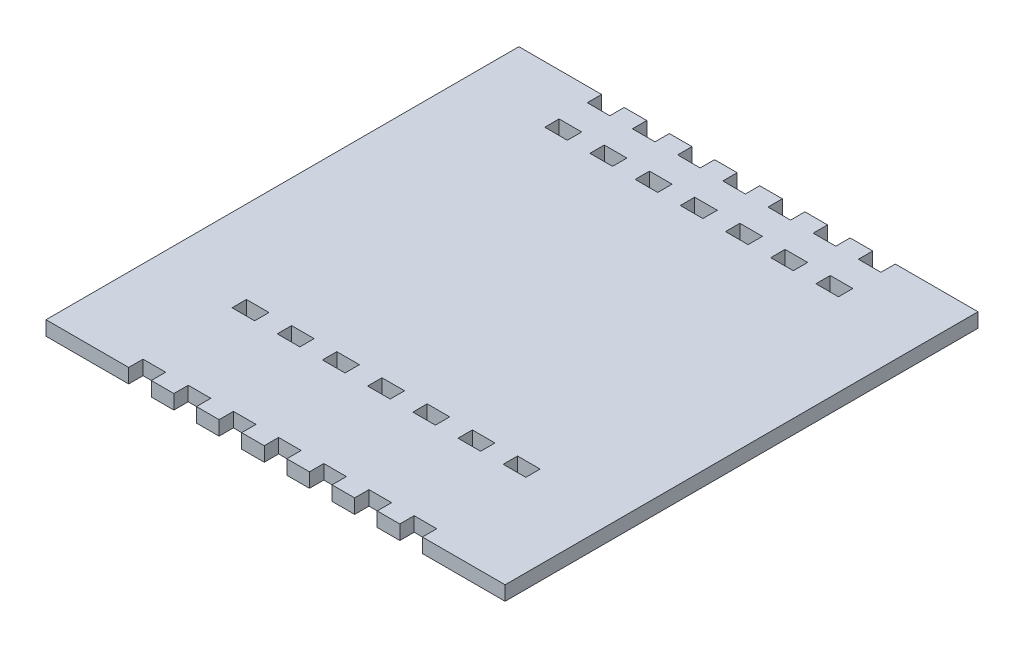
SolidWorks part; units mm, degrees
ref_plane "Front Plane" through (0, 0, 0) normal (0, 0, 1) x (1, 0, 0)
ref_plane "Top Plane" through (0, 0, 0) normal (0, 1, 0) x (1, 0, 0)
ref_plane "Right Plane" through (0, 0, 0) normal (1, 0, 0) x (0, 0, -1)
sketch "Sketch1" plane through (0, 0, 0) normal (0, 1, 0) x (1, 0, 0)
  line L0 (-34.4609, -90.3438) -> (-34.4609, -87.1688)
  line L1 (-34.4609, 14.3042) -> (-52.7609, 14.3042)
  line L2 (-52.7609, 14.3042) -> (-52.7609, -90.3438)
  line L3 (-52.7609, -90.3438) -> (-34.4609, -90.3438)
  line L4 (48.8391, 14.3042) -> (48.8391, -90.3438)
  line L5 (-34.4609, -87.1688) -> (-29.4609, -87.1688)
  line L6 (-29.4609, -87.1688) -> (-29.4609, -90.3438)
  line L7 (-19.4609, -87.1688) -> (-19.4609, -90.3438)
  line L8 (-24.4609, -87.1688) -> (-19.4609, -87.1688)
  line L9 (-24.4609, -90.3438) -> (-24.4609, -87.1688)
  line L10 (-9.4609, -87.1688) -> (-9.4609, -90.3438)
  line L11 (-14.4609, -87.1688) -> (-9.4609, -87.1688)
  line L12 (-14.4609, -90.3438) -> (-14.4609, -87.1688)
  line L13 (0.5391, -87.1688) -> (0.5391, -90.3438)
  line L14 (-4.4609, -87.1688) -> (0.5391, -87.1688)
  line L15 (-4.4609, -90.3438) -> (-4.4609, -87.1688)
  line L16 (10.5391, -87.1688) -> (10.5391, -90.3438)
  line L17 (5.5391, -87.1688) -> (10.5391, -87.1688)
  line L18 (5.5391, -90.3438) -> (5.5391, -87.1688)
  line L19 (20.5391, -87.1688) -> (20.5391, -90.3438)
  line L20 (15.5391, -87.1688) -> (20.5391, -87.1688)
  line L21 (15.5391, -90.3438) -> (15.5391, -87.1688)
  line L22 (30.5391, -87.1688) -> (30.5391, -90.3438)
  line L23 (25.5391, -87.1688) -> (30.5391, -87.1688)
  line L24 (25.5391, -90.3438) -> (25.5391, -87.1688)
  line L25 (-29.4609, -90.3438) -> (-24.4609, -90.3438)
  line L26 (-19.4609, -90.3438) -> (-14.4609, -90.3438)
  line L27 (-9.4609, -90.3438) -> (-4.4609, -90.3438)
  line L28 (0.5391, -90.3438) -> (5.5391, -90.3438)
  line L29 (10.5391, -90.3438) -> (15.5391, -90.3438)
  line L30 (20.5391, -90.3438) -> (25.5391, -90.3438)
  line L31 (30.5391, -90.3438) -> (48.8391, -90.3438)
  line L32 (-52.7609, -38.0198) -> (48.8391, -38.0198) construction
  line L33 (20.5391, 14.3042) -> (25.5391, 14.3042)
  line L34 (10.5391, 14.3042) -> (15.5391, 14.3042)
  line L35 (0.5391, 14.3042) -> (5.5391, 14.3042)
  line L36 (-9.4609, 14.3042) -> (-4.4609, 14.3042)
  line L37 (-19.4609, 14.3042) -> (-14.4609, 14.3042)
  line L38 (-29.4609, 14.3042) -> (-24.4609, 14.3042)
  line L39 (25.5391, 14.3042) -> (25.5391, 11.1292)
  line L40 (25.5391, 11.1292) -> (30.5391, 11.1292)
  line L41 (30.5391, 11.1292) -> (30.5391, 14.3042)
  line L42 (15.5391, 14.3042) -> (15.5391, 11.1292)
  line L43 (15.5391, 11.1292) -> (20.5391, 11.1292)
  line L44 (20.5391, 11.1292) -> (20.5391, 14.3042)
  line L45 (5.5391, 14.3042) -> (5.5391, 11.1292)
  line L46 (5.5391, 11.1292) -> (10.5391, 11.1292)
  line L47 (10.5391, 11.1292) -> (10.5391, 14.3042)
  line L48 (-4.4609, 14.3042) -> (-4.4609, 11.1292)
  line L49 (-4.4609, 11.1292) -> (0.5391, 11.1292)
  line L50 (0.5391, 11.1292) -> (0.5391, 14.3042)
  line L51 (-14.4609, 14.3042) -> (-14.4609, 11.1292)
  line L52 (-14.4609, 11.1292) -> (-9.4609, 11.1292)
  line L53 (-9.4609, 11.1292) -> (-9.4609, 14.3042)
  line L54 (-24.4609, 14.3042) -> (-24.4609, 11.1292)
  line L55 (-24.4609, 11.1292) -> (-19.4609, 11.1292)
  line L56 (-19.4609, 11.1292) -> (-19.4609, 14.3042)
  line L57 (-29.4609, 11.1292) -> (-29.4609, 14.3042)
  line L58 (-34.4609, 11.1292) -> (-29.4609, 11.1292)
  line L59 (-34.4609, 14.3042) -> (-34.4609, 11.1292)
  line L60 (30.5391, 14.3042) -> (48.8391, 14.3042)
  line L61 (-24.4609, 4.9062) -> (-19.4609, 4.9062)
  line L62 (-34.4609, 4.9062) -> (-29.4609, 4.9062)
  line L63 (-34.4609, 4.9062) -> (-34.4609, 1.7312)
  line L64 (-34.4609, 1.7312) -> (-29.4609, 1.7312)
  line L65 (-29.4609, 4.9062) -> (-29.4609, 1.7312)
  line L66 (-24.4609, 4.9062) -> (-24.4609, 1.7312)
  line L67 (-24.4609, 1.7312) -> (-19.4609, 1.7312)
  line L68 (-19.4609, 4.9062) -> (-19.4609, 1.7312)
  line L69 (-14.4609, 4.9062) -> (-9.4609, 4.9062)
  line L70 (-14.4609, 4.9062) -> (-14.4609, 1.7312)
  line L71 (-14.4609, 1.7312) -> (-9.4609, 1.7312)
  line L72 (-9.4609, 4.9062) -> (-9.4609, 1.7312)
  line L73 (-4.4609, 4.9062) -> (0.5391, 4.9062)
  line L74 (-4.4609, 4.9062) -> (-4.4609, 1.7312)
  line L75 (-4.4609, 1.7312) -> (0.5391, 1.7312)
  line L76 (0.5391, 4.9062) -> (0.5391, 1.7312)
  line L77 (5.5391, 4.9062) -> (10.5391, 4.9062)
  line L78 (5.5391, 4.9062) -> (5.5391, 1.7312)
  line L79 (5.5391, 1.7312) -> (10.5391, 1.7312)
  line L80 (10.5391, 4.9062) -> (10.5391, 1.7312)
  line L81 (15.5391, 4.9062) -> (20.5391, 4.9062)
  line L82 (15.5391, 4.9062) -> (15.5391, 1.7312)
  line L83 (15.5391, 1.7312) -> (20.5391, 1.7312)
  line L84 (20.5391, 4.9062) -> (20.5391, 1.7312)
  line L85 (25.5391, 4.9062) -> (30.5391, 4.9062)
  line L86 (25.5391, 4.9062) -> (25.5391, 1.7312)
  line L87 (25.5391, 1.7312) -> (30.5391, 1.7312)
  line L88 (30.5391, 4.9062) -> (30.5391, 1.7312)
  line L89 (-24.4609, -64.2948) -> (-19.4609, -64.2948)
  line L90 (-34.4609, -64.2948) -> (-29.4609, -64.2948)
  line L91 (-34.4609, -64.2948) -> (-34.4609, -67.4698)
  line L92 (-34.4609, -67.4698) -> (-29.4609, -67.4698)
  line L93 (-29.4609, -64.2948) -> (-29.4609, -67.4698)
  line L94 (-24.4609, -64.2948) -> (-24.4609, -67.4698)
  line L95 (-24.4609, -67.4698) -> (-19.4609, -67.4698)
  line L96 (-19.4609, -64.2948) -> (-19.4609, -67.4698)
  line L97 (-14.4609, -64.2948) -> (-9.4609, -64.2948)
  line L98 (-14.4609, -64.2948) -> (-14.4609, -67.4698)
  line L99 (-14.4609, -67.4698) -> (-9.4609, -67.4698)
  line L100 (-9.4609, -64.2948) -> (-9.4609, -67.4698)
  line L101 (-4.4609, -64.2948) -> (0.5391, -64.2948)
  line L102 (-4.4609, -64.2948) -> (-4.4609, -67.4698)
  line L103 (-4.4609, -67.4698) -> (0.5391, -67.4698)
  line L104 (0.5391, -64.2948) -> (0.5391, -67.4698)
  line L105 (5.5391, -64.2948) -> (10.5391, -64.2948)
  line L106 (5.5391, -64.2948) -> (5.5391, -67.4698)
  line L107 (5.5391, -67.4698) -> (10.5391, -67.4698)
  line L108 (10.5391, -64.2948) -> (10.5391, -67.4698)
  line L109 (15.5391, -64.2948) -> (20.5391, -64.2948)
  line L110 (15.5391, -64.2948) -> (15.5391, -67.4698)
  line L111 (15.5391, -67.4698) -> (20.5391, -67.4698)
  line L112 (20.5391, -64.2948) -> (20.5391, -67.4698)
  line L113 (25.5391, -64.2948) -> (30.5391, -64.2948)
  line L114 (25.5391, -64.2948) -> (25.5391, -67.4698)
  line L115 (25.5391, -67.4698) -> (30.5391, -67.4698)
  line L116 (30.5391, -64.2948) -> (30.5391, -67.4698)
  dimension "D1" = 101.6
  dimension "D2" = 104.648
  dimension "D3" = 3.175
  dimension "D4" = 5
  dimension "D6" = 10
  dimension "D7" = 3.175
  dimension "D8" = 6.223
  dimension "D9" = 5
  dimension "D11" = 10
  dimension "D12" = 3.175
  dimension "D13" = 5
  dimension "D15" = 10
  dimension "D16" = 19.699
  dimension "D5" = 7
  dimension "D10" = 7
  dimension "D14" = 7
extrude "Boss-Extrude1" add sketch "Sketch1" along normal blind 3.175
